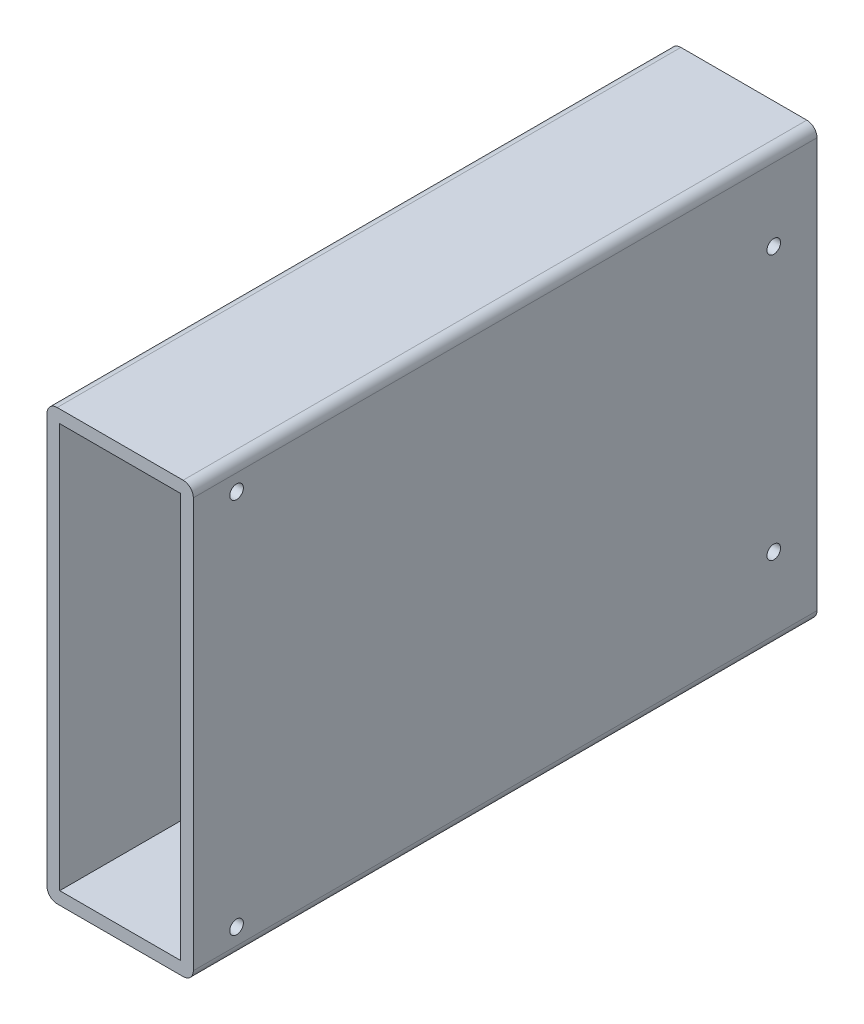
SolidWorks part; units mm, degrees
ref_plane "Front Plane" through (0, 0, 0) normal (0, 0, 1) x (1, 0, 0)
ref_plane "Top Plane" through (0, 0, 0) normal (0, 1, 0) x (1, 0, 0)
ref_plane "Right Plane" through (0, 0, 0) normal (1, 0, 0) x (0, 0, -1)
sketch "Sketch1" plane through (0, 0, 0) normal (1, 0, 0) x (0, 0, -1)
  line L1 (0, 0) -> (155.575, 0)
  line L2 (0, 0) -> (0, 107.2375)
  line L3 (0, 107.2375) -> (155.575, 107.2375)
  line L4 (155.575, 0) -> (155.575, 107.2375)
  dimension "D1" = 155.575
  dimension "D2" = 107.2375
extrude "Boss-Extrude1" add sketch "Sketch1" along normal blind 36.5
shell "Shell2" thickness 3.175
fillet "Fillet1" radius 2.54 4 edges at (36.5, 0, -77.7875) (0, 0, -77.7875) (0, 107.2375, -77.7875) (36.5, 107.2375, -77.7875)
sketch "Sketch7" plane through (0, 0, -155.575) normal (0, 0, -1) x (-1, 0, 0)
  line L1 (-13.175, 35) -> (-28.175, 35)
  line L2 (-13.175, 35) -> (-13.175, 20)
  line L3 (-13.175, 20) -> (-28.175, 20)
  line L4 (-28.175, 35) -> (-28.175, 20)
  circle A0 centre (-7.175, 30) radius 1.2 construction
  circle A1 centre (-7.175, 5) radius 1.2 construction
  circle A2 centre (-7.175, 30) radius 1.2
  circle A3 centre (-7.175, 5) radius 1.2
  dimension "D1" = 15
extrude "Cut-Extrude2" cut sketch "Sketch7" against normal up to next
sketch "Sketch8" plane through (0, 0, -152.4) normal (0, 0, 1) x (1, 0, 0)
  line L1 (33.325, 3.175) -> (3.175, 3.175) construction
  line L2 (3.175, 3.175) -> (3.175, 104.0625) construction
  circle A0 centre (7.175, 25.4) radius 2.3813
  circle A1 centre (7.175, 5) radius 1.2 construction
  circle A2 centre (7.175, 5) radius 1.2 construction
  dimension "D2" = 4.7625
  dimension "D1" = 22.225
  dimension "D3" = 4
extrude "Cut-Extrude3" cut sketch "Sketch8" against normal through all
hole_wizard "M3 Clearance Hole1" positions "Sketch14" profile "Sketch11" hole size "M3" standard "ANSI Metric"
sketch "Sketch14" plane through (36.5, 0, 0) normal (1, 0, 0) x (0, 0, -1)
  point P0 (144.7875, 86.6188)
  point P2 (144.7875, 20.6188)
  point P4 (10.7875, 6.6188)
  point P6 (10.7875, 100.6188)
  point P10 (10.7875, 100.6188)
  point P11 (10.7875, 6.6188)
  point P12 (144.7875, 20.6188)
  point P13 (144.7875, 86.6188)
sketch "Sketch11" plane through (36.5, 86.6188, -144.7875) normal (0, 1, 0) x (0, 0, -1)
  line L0 (0, 0) -> (0, 3.175)
  line L1 (0, 3.175) -> (1.7, 3.175)
  line L2 (1.7, 3.175) -> (1.7, 0)
  line L5 (1.7, 0) -> (0, 0)
  line L11 (0, -6.35) -> (0, 107.95) construction
  dimension "Thru Hole Dia." = 3.4
  dimension "Thru Hole Depth" = 3.175
equation "\"D2@Sketch1\"=4.1875in+.875mm"
